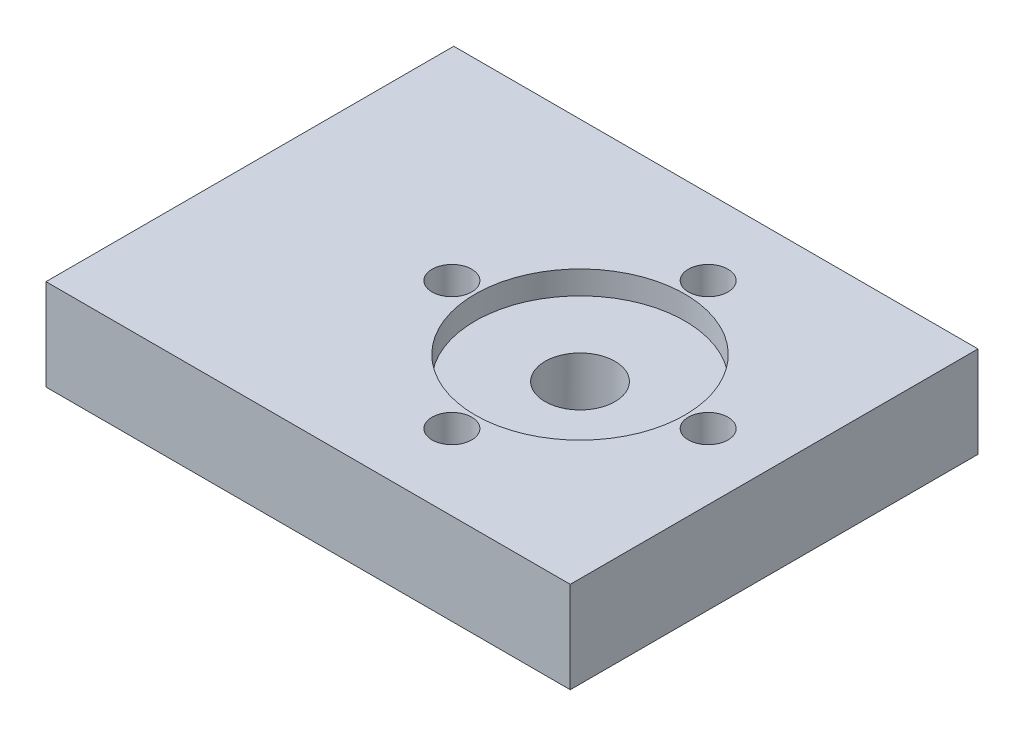
SolidWorks part; units mm, degrees
ref_plane "Front Plane" through (0, 0, 0) normal (0, 0, 1) x (1, 0, 0)
ref_plane "Top Plane" through (0, 0, 0) normal (0, 1, 0) x (1, 0, 0)
ref_plane "Right Plane" through (0, 0, 0) normal (1, 0, 0) x (0, 0, -1)
sketch "Sketch1" plane through (0, 0, 0) normal (0, 1, 0) x (1, 0, 0)
  line L1 (-22.5, -17.5) -> (22.5, -17.5)
  line L2 (-22.5, -17.5) -> (-22.5, 17.5)
  line L3 (-22.5, 17.5) -> (22.5, 17.5)
  line L4 (22.5, -17.5) -> (22.5, 17.5)
  line L5 (-22.5, -17.5) -> (22.5, 17.5) construction
  line L6 (-22.5, 17.5) -> (22.5, -17.5) construction
  point P0 (0, 0)
  dimension "D1" = 45
  dimension "D2" = 35
extrude "Boss-Extrude1" add sketch "Sketch1" along normal blind 7.8384
sketch "Sketch4" plane through (0, 7.8384, 0) normal (0, 1, 0) x (1, 0, 0)
  line L0 (-55, 0) -> (55, 0) construction
  line L1 (22.5, -17.5) -> (22.5, 17.5) construction
  circle A1 centre (5.84, 0) radius 9
  dimension "D1" = 18
  dimension "D2" = 16.66
extrude "Cut-Extrude3" cut sketch "Sketch4" against normal blind 2
sketch "Sketch5" plane through (0, 7.8384, 0) normal (0, 1, 0) x (1, 0, 0)
  line L1 (22.5, 17.5) -> (-22.5, 17.5) construction
  circle A0 centre (5.84, 0) radius 9 construction
  circle A1 centre (5.84, 0) radius 11 construction
  circle A2 centre (5.84, 11) radius 1.7
  circle A4 centre (16.84, 0) radius 1.7
  circle A5 centre (5.84, -11) radius 1.7
  circle A6 centre (-5.16, 0) radius 1.7
  circle A7 centre (5.84, 0) radius 3
  point P12 (5.84, -8.4862)
  dimension "D1" = 3.4
  dimension "D3" = 22
  dimension "D2" = 6.5
  dimension "D5" = 6
  dimension "D4" = 4
extrude "Cut-Extrude4" cut sketch "Sketch5" against normal up to surface (7.8384 mm away) up to face at (0, 0, 0)
equation "\"Force\"= 300"
equation "\"Saftey Factor\"= 3"
equation "\"Saftey Factor Force\"= \"Force\" * \"Saftey Factor\""
equation "\"Shaft Length\"= 18"
equation "\"Moment\"= \"Saftey Factor Force\" * \"Shaft Length\""
equation "\"Base\"= 35"
equation "\"Yield Strength\"= 45.2"
equation "\"Height\"= SQR ( ( 6 * \"Moment\" ) / ( \"Base\" * \"Yield Strength\" ) )"
equation "\"Length\"= 45"
equation "\"D2@Sketch1\"=\"Base\""
equation "\"D1@Sketch1\"=\"Length\""
equation "\"D1@Boss-Extrude1\"=\"Height\""
equation "\"D1@Sketch4\"=\"Shaft Length\""
